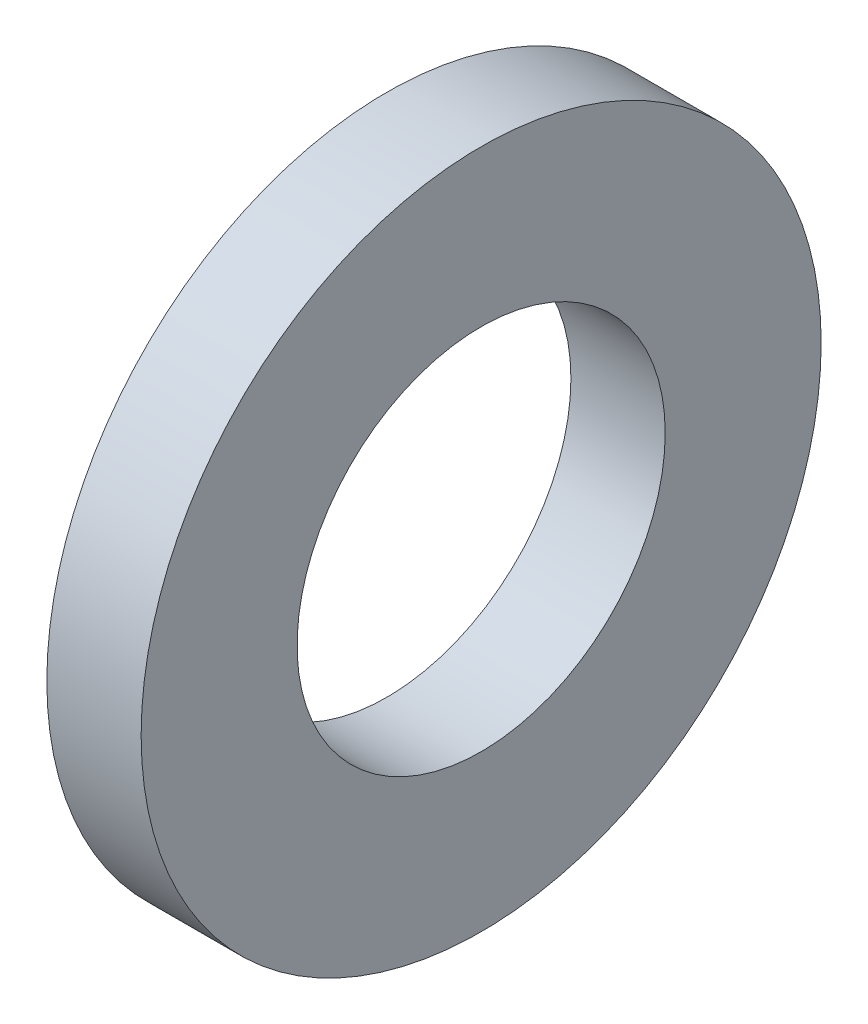
SolidWorks part; units mm, degrees
ref_plane "Front Plane" through (0, 0, 0) normal (0, 0, 1) x (1, 0, 0)
ref_plane "Top Plane" through (0, 0, 0) normal (0, 1, 0) x (1, 0, 0)
ref_plane "Right Plane" through (0, 0, 0) normal (1, 0, 0) x (0, 0, -1)
sketch "Sketch1" plane through (0, 0, 0) normal (1, 0, 0) x (0, 0, -1)
  circle A0 centre (0, 0) radius 2.5781
  circle A1 centre (0, 0) radius 4.7625
  dimension "OD" = 5.1562
  dimension "ID" = 9.525
extrude "Boss-Extrude1" add sketch "Sketch1" along normal blind 1.3208
